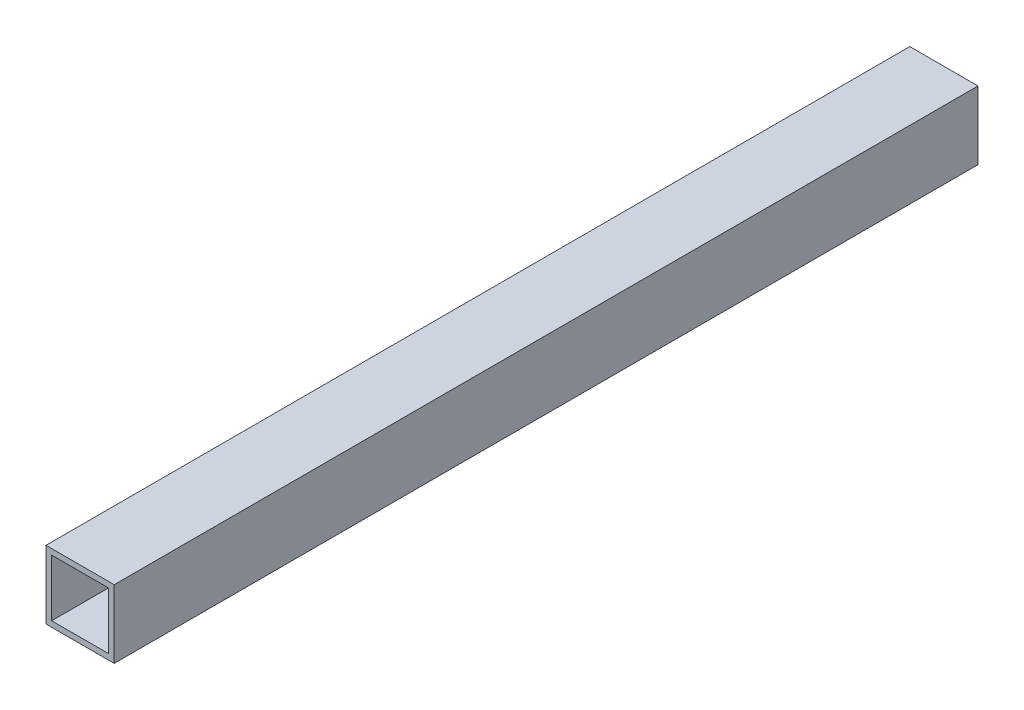
SolidWorks part; units mm, degrees
ref_plane "Front Plane" through (0, 0, 0) normal (0, 0, 1) x (1, 0, 0)
ref_plane "Top Plane" through (0, 0, 0) normal (0, 1, 0) x (1, 0, 0)
ref_plane "Right Plane" through (0, 0, 0) normal (1, 0, 0) x (0, 0, -1)
sketch "Sketch1" plane through (0, 0, 0) normal (0, 0, 1) x (1, 0, 0)
  line L0 (19.05, 0) -> (15.875, 0) construction
  line L1 (-19.05, 0) -> (19.05, 0) construction
  line L2 (0, 19.05) -> (0, -19.05)
  point P7 (0, 0)
sketch "Sketch2" plane through (0, 0, 0) normal (1, 0, 0) x (0, 0, -1)
  line L0 (241.3, 0) -> (-241.3, 0)
  point P4 (0, 0)
  dimension "Length" = 482.6
sketch "Sketch3" plane through (0, 0, 0) normal (0, 0, 1) x (1, 0, 0)
  line L0 (-19.05, 0) -> (19.05, 0) construction
  line L5 (19.05, -19.05) -> (-19.05, -19.05)
  line L6 (19.05, -19.05) -> (19.05, 19.05)
  line L11 (19.05, 19.05) -> (-19.05, 19.05)
  line L12 (-19.05, -19.05) -> (-19.05, 19.05)
  line L14 (19.05, -19.05) -> (-19.05, 19.05) construction
  line L15 (19.05, 19.05) -> (-19.05, -19.05) construction
  line L16 (15.875, -15.875) -> (-15.875, -15.875)
  line L17 (15.875, -15.875) -> (15.875, 15.875)
  line L18 (15.875, 15.875) -> (-15.875, 15.875)
  line L19 (-15.875, -15.875) -> (-15.875, 15.875)
  line L20 (15.875, -15.875) -> (-15.875, 15.875) construction
  line L21 (15.875, 15.875) -> (-15.875, -15.875) construction
  point P0 (0, 0)
  point P5 (0, 0)
  point P13 (15.875, -19.05)
  dimension "D1" = 3.175
  dimension "D3" = 38.1
  dimension "D4" = 38.1
  dimension "D2" = 3.175
extrude "Boss-Extrude1" add sketch "Sketch3" along normal up to vertex (241.3 mm away) and the other way up to vertex (241.3 mm away) up to point (0, 0, 241.3) other way up to point (0, 0, -241.3)
sketch "Sketch5" plane through (0, 0, 0) normal (1, 0, 0) x (0, 0, -1)
  line L0 (-241.3, 0) -> (241.3, 0) construction
  line L3 (-241.3, -19.05) -> (-241.3, 19.05) construction
  line L4 (241.3, -19.05) -> (241.3, 19.05) construction
  point P6 (-198.4375, 0)
  point P7 (-184.15, 0)
  point P8 (184.15, 0)
  point P10 (198.4375, 0)
  dimension "D1" = 42.8625
  dimension "D2" = 57.15
  dimension "D3" = 42.8625
  dimension "D4" = 57.15
equation "\"D1@Sketch3\"=\"Wall thickness@Sketch1\""
equation "\"D1@Sketch5\"=\"Width@Sketch1\"*1.125"
equation "\"D2@Sketch5\"=\"Width@Sketch1\"*1.5"
equation "\"D3@Sketch5\"=\"D1@Sketch5\""
equation "\"D4@Sketch5\"=\"D2@Sketch5\""
equation "\"D2@Sketch3\"=\"Wall Thickness@Sketch1\""
